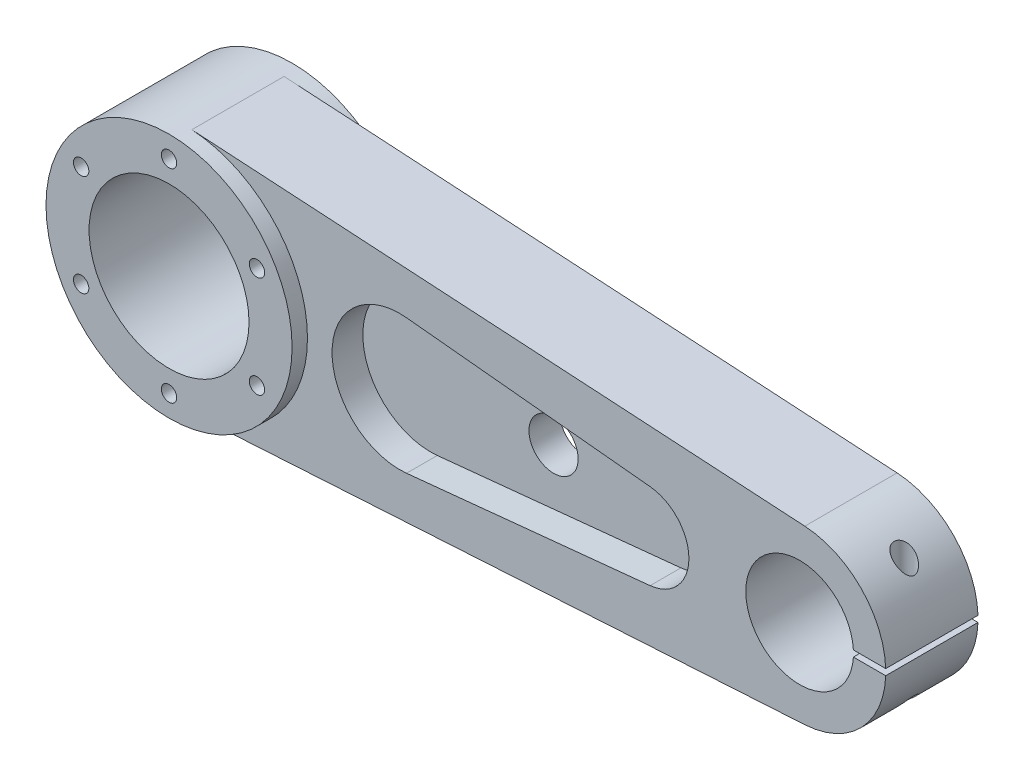
SolidWorks part; units mm, degrees
ref_plane "前视基准面" through (0, 0, 0) normal (0, 0, 1) x (1, 0, 0)
ref_plane "上视基准面" through (0, 0, 0) normal (0, 1, 0) x (1, 0, 0)
ref_plane "右视基准面" through (0, 0, 0) normal (1, 0, 0) x (0, 0, -1)
ref_plane "基准面1" through (0, 0, 5) normal (0, 0, 1) x (1, 0, 0)
sketch "草图1" plane through (0, 0, 5) normal (0, 0, 1) x (1, 0, 0)
  line L0 (2.4, -39.9279) -> (201.68, -27.9496)
  line L1 (201.68, 27.9496) -> (2.4, 39.9279)
  arc A0 (201.68, -27.9496) -> (201.68, 27.9496) centre (200, 0) ccw
  arc A1 (2.4, 39.9279) -> (2.4, -39.9279) centre (0, 0) ccw
extrude "凸台-拉伸1" add sketch "草图1" along normal blind 30
sketch "草图2" plane through (0, 0, 0) normal (0, 0, 1) x (1, 0, 0)
  circle A0 centre (0, 0) radius 40
extrude "凸台-拉伸2" add sketch "草图2" along normal blind 40
ref_plane "基准面2" through (0, 0, 25) normal (0, 0, 1) x (1, 0, 0)
sketch "草图3" plane through (0, 0, 25) normal (0, 0, 1) x (1, 0, 0)
  line L0 (72.2, -21.8897) -> (151.4, -13.9298)
  line L1 (151.4, 13.9298) -> (72.2, 21.8897)
  arc A0 (151.4, -13.9298) -> (151.4, 13.9298) centre (150, 0) ccw
  arc A1 (72.2, 21.8897) -> (72.2, -21.8897) centre (70, 0) ccw
extrude "切除-拉伸1" cut sketch "草图3" along normal blind 10
sketch "草图4" plane through (0, 0, 5) normal (0, 0, 1) x (1, 0, 0)
  line L0 (72.2, -21.8897) -> (151.4, -13.9298)
  line L1 (151.4, 13.9298) -> (72.2, 21.8897)
  arc A0 (151.4, -13.9298) -> (151.4, 13.9298) centre (150, 0) ccw
  arc A1 (72.2, 21.8897) -> (72.2, -21.8897) centre (70, 0) ccw
extrude "切除-拉伸2" cut sketch "草图4" along normal blind 10
sketch "草图5" plane through (0, 0, 0) normal (0, 0, 1) x (1, 0, 0)
  circle A0 centre (0, 0) radius 26
extrude "切除-拉伸3" cut sketch "草图5" against normal mid plane 538
sketch "草图6" plane through (0, 0, 0) normal (0, 0, 1) x (1, 0, 0)
  circle A0 centre (200, 0) radius 17.5
extrude "切除-拉伸4" cut sketch "草图6" against normal mid plane 538
ref_plane "基准面3" through (0, 0, 15) normal (0, 0, 1) x (1, 0, 0)
sketch "草图7" plane through (0, 0, 15) normal (0, 0, 1) x (1, 0, 0)
  circle A0 centre (110, 0) radius 8
extrude "切除-拉伸5" cut sketch "草图7" against normal mid plane 538
ref_plane "基准面4" through (0, 0, 40) normal (0, 0, 1) x (1, 0, 0)
ref_plane "基准面5" through (0, 0, 20) normal (0, 0, 1) x (1, 0, 0)
sketch "草图9" plane through (0, 0, 20) normal (0, 0, 1) x (1, 0, 0)
  line L0 (200, -1) -> (230, -1)
  line L1 (230, -1) -> (230, 1)
  line L2 (230, 1) -> (200, 1)
  line L3 (200, 1) -> (200, -1)
extrude "切除-拉伸8" cut sketch "草图9" against normal mid plane 538
sketch "草图10" plane through (0, 0, 40) normal (0, 0, 1) x (1, 0, 0)
  circle A0 centre (28.5788, 16.5) radius 2.5
  circle A1 centre (0, 33) radius 2.5
  circle A2 centre (-28.5788, 16.5) radius 2.5
  circle A3 centre (-28.5788, -16.5) radius 2.5
  circle A4 centre (0, -33) radius 2.5
  circle A5 centre (28.5788, -16.5) radius 2.5
extrude "切除-拉伸9" cut sketch "草图10" against normal blind 12
sketch "草图11" plane through (0, 0, 0) normal (0, 1, 0) x (1, 0, 0)
  circle A0 centre (219, -20) radius 3.3
extrude "切除-拉伸10" cut sketch "草图11" against normal mid plane 537.964
